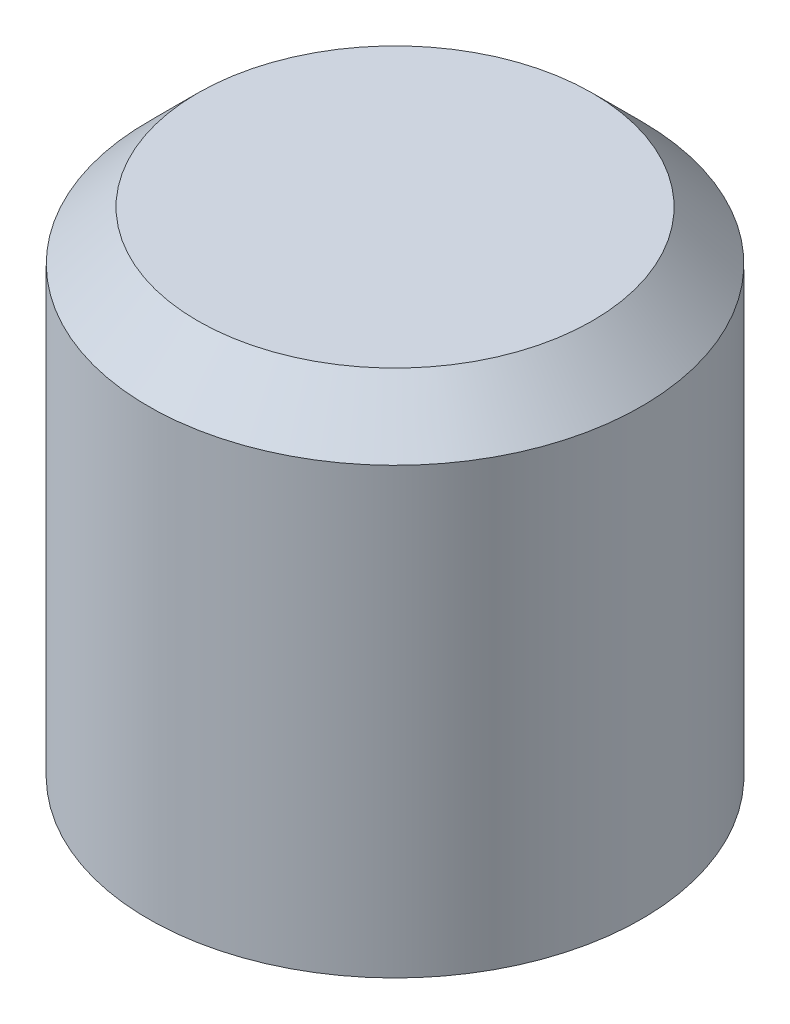
SolidWorks part; units mm, degrees
ref_plane "Front Plane" through (0, 0, 0) normal (0, 0, 1) x (1, 0, 0)
ref_plane "Top Plane" through (0, 0, 0) normal (0, 1, 0) x (1, 0, 0)
ref_plane "Right Plane" through (0, 0, 0) normal (1, 0, 0) x (0, 0, -1)
ref_plane "plane:xy" through (0, 0, 0) normal (0, 0, 1) x (1, 0, 0)
sketch "sketch:profile" plane through (0, 0, 0) normal (0, 0, 1) x (1, 0, 0)
  line L0 (0, 0) -> (10, 0)
  line L1 (10, 0) -> (10, 18)
  line L2 (10, 18) -> (8, 20)
  line L3 (8, 20) -> (0, 20)
  line L4 (0, 20) -> (0, 0)
  line L5 (0, -10) -> (0, 30) construction
revolve "feature:turned" add sketch "sketch:profile" angle 360 about L5
